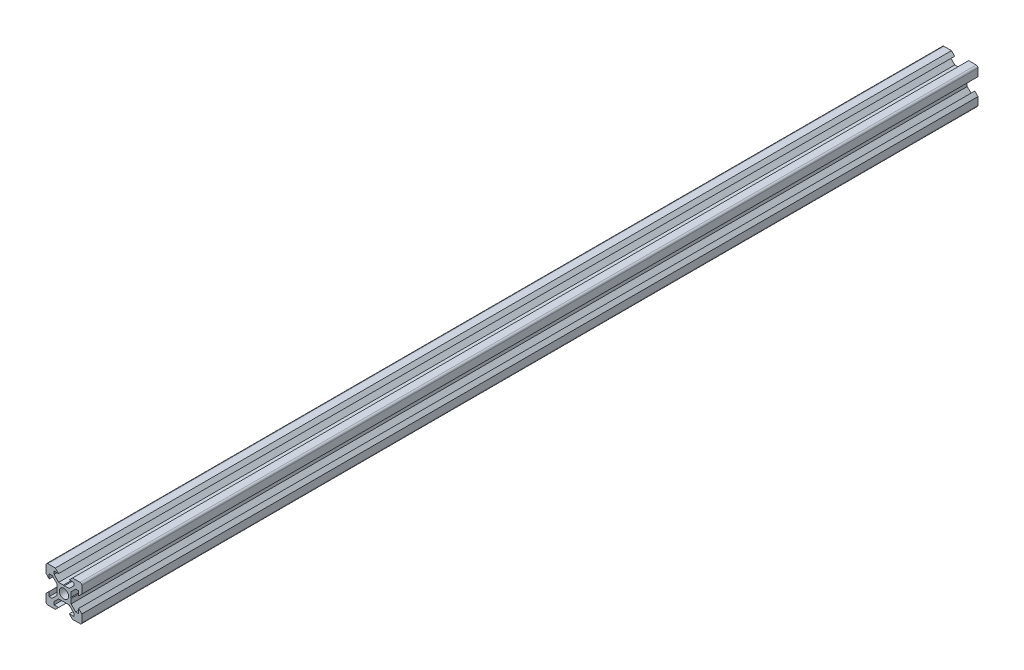
SolidWorks part; units mm, degrees
material "1060-H12 Rod (SS)"
ref_plane "Front Plane" through (0, 0, 0) normal (0, 0, 1) x (1, 0, 0)
ref_plane "Top Plane" through (0, 0, 0) normal (0, 1, 0) x (1, 0, 0)
ref_plane "Right Plane" through (0, 0, 0) normal (1, 0, 0) x (0, 0, -1)
sketch "Sketch1" plane through (0, 0, 0) normal (0, 0, 1) x (1, 0, 0)
  line B0 (10.3368, -8.1134) -> (10.3368, -3.9134)
  line B1 (10.3368, -3.9134) -> (8.5368, -2.1134)
  line B2 (8.5368, -2.1134) -> (8.5368, -4.6134)
  line B3 (8.5368, -4.6134) -> (6.8974, -4.6134)
  line B4 (6.8974, -4.6134) -> (4.3368, -2.0527)
  line B5 (4.3368, -2.0527) -> (4.3368, 0.5866)
  line B6 (4.3368, 0.5866) -> (4.0368, 0.8866)
  line B7 (4.0368, 0.8866) -> (4.3368, 1.1866)
  line B8 (4.3368, 1.1866) -> (4.3368, 3.826)
  line B9 (4.3368, 3.826) -> (6.8974, 6.3866)
  line B10 (6.8974, 6.3866) -> (8.5368, 6.3866)
  line B11 (8.5368, 6.3866) -> (8.5368, 3.8866)
  line B12 (8.5368, 3.8866) -> (10.3368, 5.6866)
  line B13 (10.3368, 5.6866) -> (10.3368, 9.8866)
  line B14 (9.3368, 10.8866) -> (5.1368, 10.8866)
  line B15 (5.1368, 10.8866) -> (3.3368, 9.0866)
  line B16 (3.3368, 9.0866) -> (5.8368, 9.0866)
  line B17 (5.8368, 9.0866) -> (5.8368, 7.4473)
  line B18 (5.8368, 7.4473) -> (3.2761, 4.8866)
  line B19 (3.2761, 4.8866) -> (0.6368, 4.8866)
  line B20 (0.6368, 4.8866) -> (0.3368, 4.5866)
  line B21 (0.3368, 4.5866) -> (0.0368, 4.8866)
  line B22 (0.0368, 4.8866) -> (-2.6026, 4.8866)
  line B23 (-2.6026, 4.8866) -> (-5.1632, 7.4473)
  line B24 (-5.1632, 7.4473) -> (-5.1632, 9.0866)
  line B25 (-5.1632, 9.0866) -> (-2.6632, 9.0866)
  line B26 (-2.6632, 9.0866) -> (-4.4632, 10.8866)
  line B27 (-4.4632, 10.8866) -> (-8.6632, 10.8866)
  line B28 (-9.6632, 9.8866) -> (-9.6632, 5.6866)
  line B29 (-9.6632, 5.6866) -> (-7.8632, 3.8866)
  line B30 (-7.8632, 3.8866) -> (-7.8632, 6.3866)
  line B31 (-7.8632, 6.3866) -> (-6.2239, 6.3866)
  line B32 (-6.2239, 6.3866) -> (-3.6632, 3.826)
  line B33 (-3.6632, 3.826) -> (-3.6632, 1.1866)
  line B34 (-3.6632, 1.1866) -> (-3.3632, 0.8866)
  line B35 (-3.3632, 0.8866) -> (-3.6632, 0.5866)
  line B36 (-3.6632, 0.5866) -> (-3.6632, -2.0527)
  line B37 (-3.6632, -2.0527) -> (-6.2239, -4.6134)
  line B38 (-6.2239, -4.6134) -> (-7.8632, -4.6134)
  line B39 (-7.8632, -4.6134) -> (-7.8632, -2.1134)
  line B40 (-7.8632, -2.1134) -> (-9.6632, -3.9134)
  line B41 (-9.6632, -3.9134) -> (-9.6632, -8.1134)
  line B42 (-8.6632, -9.1134) -> (-4.4632, -9.1134)
  line B43 (-4.4632, -9.1134) -> (-2.6632, -7.3134)
  line B44 (-2.6632, -7.3134) -> (-5.1632, -7.3134)
  line B45 (-5.1632, -7.3134) -> (-5.1632, -5.674)
  line B46 (-5.1632, -5.674) -> (-2.6026, -3.1134)
  line B47 (-2.6026, -3.1134) -> (0.0368, -3.1134)
  line B48 (0.0368, -3.1134) -> (0.3368, -2.8134)
  line B49 (0.3368, -2.8134) -> (0.6368, -3.1134)
  line B50 (0.6368, -3.1134) -> (3.2761, -3.1134)
  line B51 (3.2761, -3.1134) -> (5.8368, -5.674)
  line B52 (5.8368, -5.674) -> (5.8368, -7.3134)
  line B53 (5.8368, -7.3134) -> (3.3368, -7.3134)
  line B54 (3.3368, -7.3134) -> (5.1368, -9.1134)
  line B55 (5.1368, -9.1134) -> (9.3368, -9.1134)
  arc B56 (9.3368, -9.1134) -> (10.3368, -8.1134) centre (9.3368, -8.1134) ccw
  arc B57 (10.3368, 9.8866) -> (9.3368, 10.8866) centre (9.3368, 9.8866) ccw
  arc B58 (-8.6632, 10.8866) -> (-9.6632, 9.8866) centre (-8.6632, 9.8866) ccw
  arc B59 (-9.6632, -8.1134) -> (-8.6632, -9.1134) centre (-8.6632, -8.1134) ccw
  circle B60 centre (0.3368, 0.8866) radius 2.6
sketch_block_instance "AL profile  block  -1"
sketch_block "AL profile  block  " parameters "D1"=3.2452
extrude "Boss-Extrude1" add sketch "Sketch1" along normal blind 500
